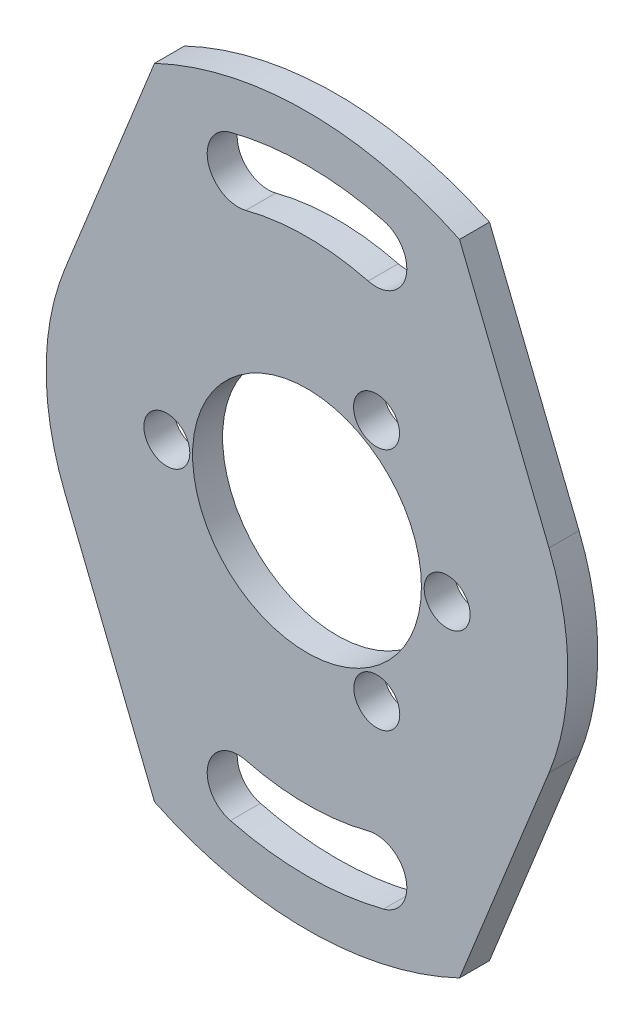
SolidWorks part; units mm, degrees
ref_plane "Front Plane" through (0, 0, 0) normal (0, 0, 1) x (1, 0, 0)
ref_plane "Top Plane" through (0, 0, 0) normal (0, 1, 0) x (1, 0, 0)
ref_plane "Right Plane" through (0, 0, 0) normal (1, 0, 0) x (0, 0, -1)
sketch "Sketch2" plane through (0, 0, 0) normal (0, 0, 1) x (1, 0, 0)
  line L0 (0, -36.8665) -> (0, 36.1524)
  line L5 (-8.135, -55.5232) -> (-8.135, 53.3893) construction
  line L6 (8.135, -62.784) -> (8.135, 68.0592) construction
  line L7 (-8.135, -17.0597) -> (-28.3213, 33.1099)
  line L8 (-29.3025, -35.5484) -> (-8.135, 17.0597)
  line L9 (8.135, -17.0597) -> (24.7023, 24.1154)
  line L10 (23.4874, -21.0962) -> (8.135, 17.0597)
  line L11 (-55.3867, 0) -> (45.5519, 0) construction
  line L12 (3.675, 14.3003) -> (-3.675, 14.3003) construction
  line L13 (3.675, 14.3003) -> (3.675, -14.3003) construction
  line L14 (3.675, -14.3003) -> (-3.675, -14.3003) construction
  line L15 (-3.675, 14.3003) -> (-3.675, -14.3003) construction
  line L16 (3.675, 14.3003) -> (-3.675, -14.3003) construction
  line L17 (3.675, -14.3003) -> (-3.675, 14.3003) construction
  circle A0 centre (0, 0) radius 10.8541
  circle A1 centre (3.7087, 6.4913) radius 1.2248
  circle A2 centre (7.4761, 0) radius 1.2248
  circle A3 centre (3.7233, -6.4829) radius 1.2248
  circle A4 centre (-7.4761, 0) radius 1.2248
  circle A5 centre (0, 0) radius 6.1038
  arc A6 (-8.135, -17.0597) -> (8.135, -17.0597) centre (0, 0) ccw
  circle A7 centre (0, 0) radius 13.915
  arc A10 (8.135, 17.0597) -> (-8.135, 17.0597) centre (0, 0) ccw
  circle A11 centre (0, 0) radius 14.765
  arc A12 (3.675, -14.3003) -> (-3.675, -14.3003) centre (0, 0) cw construction
  arc A13 (-4.0857, -15.8984) -> (4.0857, -15.8984) centre (0, 0) ccw
  arc A14 (-3.2643, -12.7023) -> (3.2643, -12.7023) centre (0, 0) ccw
  arc A15 (-3.2643, -12.7023) -> (-4.0857, -15.8984) centre (-3.675, -14.3003) ccw
  arc A16 (4.0857, -15.8984) -> (3.2643, -12.7023) centre (3.675, -14.3003) ccw
  arc A17 (3.675, 14.3003) -> (-3.675, 14.3003) centre (0, 0) ccw construction
  arc A18 (-4.0857, 15.8984) -> (4.0857, 15.8984) centre (0, 0) cw
  arc A19 (-3.2643, 12.7023) -> (3.2643, 12.7023) centre (0, 0) cw
  arc A20 (-3.2643, 12.7023) -> (-4.0857, 15.8984) centre (-3.675, 14.3003) cw
  arc A21 (4.0857, 15.8984) -> (3.2643, 12.7023) centre (3.675, 14.3003) cw
  circle A22 centre (0, 0) radius 7.4761 construction
  point P15 (0, -14.765)
  point P23 (-8.135, -17.0597)
  point P24 (8.135, 17.0597)
  point P25 (-8.135, 17.0597)
  point P27 (8.135, -17.0597)
  point P38 (0, -14.765)
  point P44 (-5.325, -14.3003)
  point P45 (5.325, -14.3003)
  point P49 (0, 14.765)
  point P54 (0, 0)
  point P55 (0, 0)
  point P56 (0, 0)
  point P57 (0, 0)
  point P58 (0, 0)
  point P59 (0, 0)
  point P60 (0, 0)
  point P61 (0, 0)
  dimension "D1" = 37.8
  dimension "D2" = 27.83
  dimension "D5" = 29.53
  dimension "D6" = 3.3
  dimension "D7" = 7.35
  dimension "D8" = 14.9521
  dimension "D3" = 16.27
  dimension "D4" = 8.135
extrude "Boss-Extrude1" add sketch "Sketch2" along normal blind 1.6 contours A15 A11 L7 A6 L0 A13 | A16 A13 L0 A6 L9 A11 | A16 A11 L9 A7 | A15 A7 L7 A11 | A19 A20 A7 A15 A14 L0 A0 | A7 A20 A11 L8 | A11 A20 A18 L0 A10 L8 | A11 A21 A7 L10 | A7 A21 A19 L0 A0 A14 A16 | A18 A21 A11 L10 A10 L0 | A5 L0 A0 A4 | A5 L0 A0 A3 A2 A1
